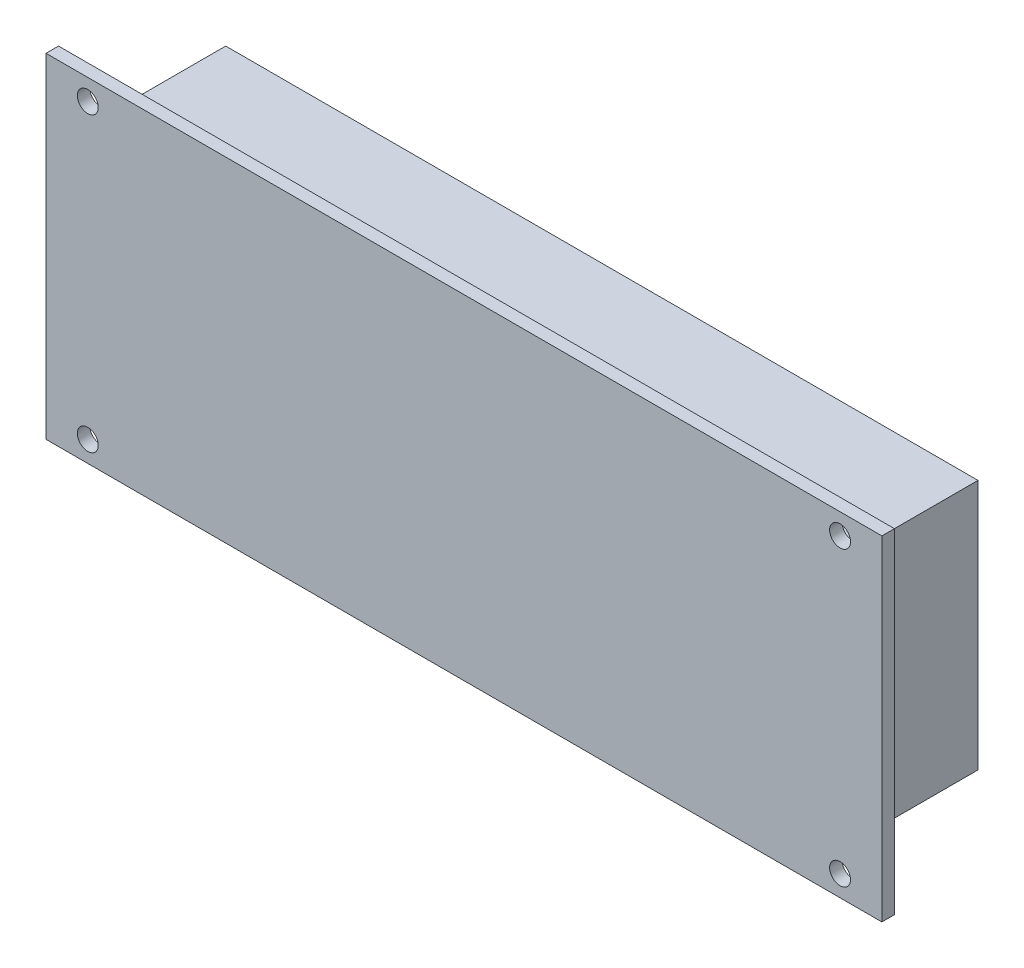
SolidWorks part; units mm, degrees
ref_plane "前视基准面" through (0, 0, 0) normal (0, 0, 1) x (1, 0, 0)
ref_plane "上视基准面" through (0, 0, 0) normal (0, 1, 0) x (1, 0, 0)
ref_plane "右视基准面" through (0, 0, 0) normal (1, 0, 0) x (0, 0, -1)
sketch "草图1" plane through (0, 0, 0) normal (0, 0, 1) x (1, 0, 0)
  line L1 (-100, -40) -> (100, -40)
  line L2 (-100, -40) -> (-100, 40)
  line L3 (-100, 40) -> (100, 40)
  line L4 (100, -40) -> (100, 40)
  line L5 (-100, -40) -> (100, 40) construction
  line L6 (-100, 40) -> (100, -40) construction
  point P0 (0, 0)
  dimension "D1" = 200
  dimension "D2" = 80
extrude "凸台-拉伸1" add sketch "草图1" along normal blind 3
sketch "草图2" plane through (0, 0, 0) normal (0, 0, -1) x (-1, 0, 0)
  line L1 (-90, -30) -> (90, -30)
  line L2 (-90, -30) -> (-90, 30)
  line L3 (-90, 30) -> (90, 30)
  line L4 (90, -30) -> (90, 30)
  line L5 (-90, -30) -> (90, 30) construction
  line L6 (-90, 30) -> (90, -30) construction
  point P0 (0, 0)
  dimension "D1" = 180
  dimension "D2" = 60
extrude "凸台-拉伸2" add sketch "草图2" along normal blind 30
sketch "草图3" plane through (0, 0, 0) normal (0, 0, -1) x (-1, 0, 0)
  line L0 (-90, -40) -> (-90, -35)
  line L1 (-100, 40) -> (100, 40) construction
  line L2 (-90, 40) -> (-90, 35)
  line L3 (0, 40) -> (0, 34.352) construction
  line L4 (-100, 0) -> (-93.3033, 0) construction
  line L5 (-100, -40) -> (-100, 40) construction
  line L6 (90, -40) -> (90, -35)
  line L7 (90, 40) -> (90, 35)
  dimension "D2" = 5
hole_wizard "M6 螺纹孔1" positions "草图4" profile "草图5" tap size "M6" standard "GB"
sketch "草图4" plane through (0, 0, 0) normal (0, 0, -1) x (-1, 0, 0)
  point P0 (-90, 35)
  point P3 (-90, -35)
  point P6 (90, -35)
  point P9 (90, 35)
sketch "草图5" plane through (90, 35, 0) normal (1, 0, 0) x (0, 1, 0)
  line L0 (0, 0) -> (0, 16.5022)
  line L1 (0, 16.5022) -> (2.5, 15)
  line L2 (2.5, 15) -> (2.5, 0)
  line L5 (2.5, 0) -> (0, 0)
  line L10 (0, 16.5022) -> (-2.5, 15) construction
  line L11 (0, -6.35) -> (0, 107.95) construction
  dimension "螺纹孔钻头直径" = 5
  dimension "螺纹孔钻头深度" = 15
  dimension "导头角度" = 118
cosmetic thread "孔螺纹线1" parameters "D1"=12, "D2"=6
cosmetic thread "孔螺纹线2" parameters "D1"=12, "D2"=6
cosmetic thread "孔螺纹线3" parameters "D1"=12, "D2"=6
cosmetic thread "孔螺纹线4" parameters "D1"=12, "D2"=6
